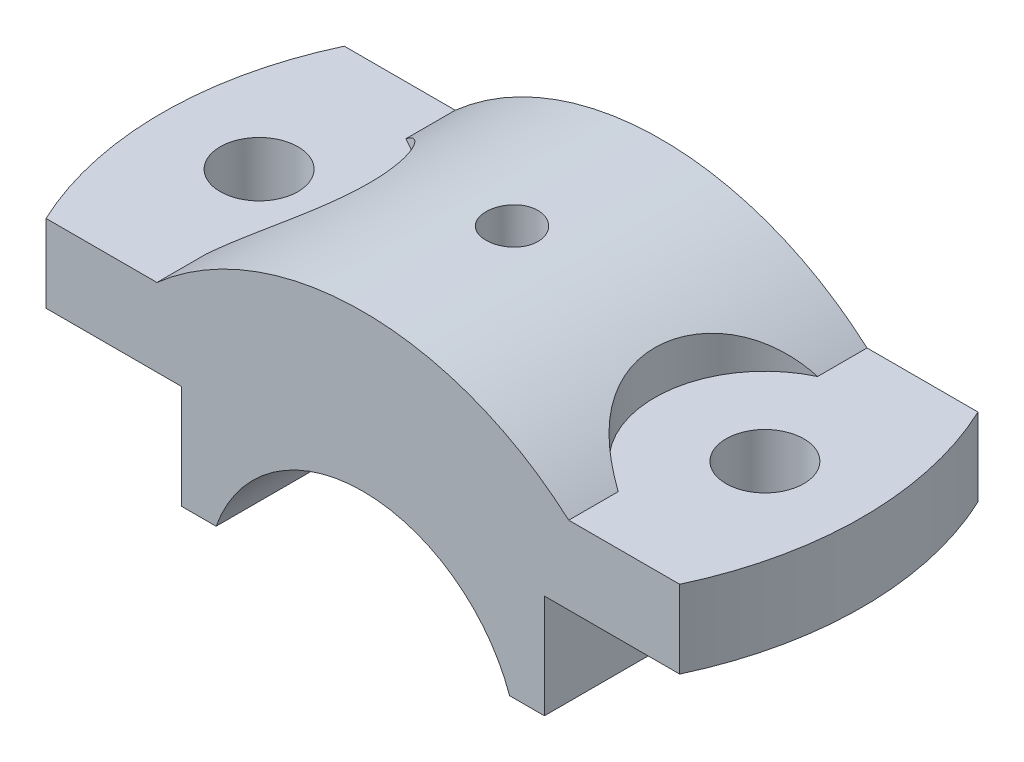
SolidWorks part; units mm, degrees
material "Gray Cast Iron"
ref_plane "Front Plane" through (0, 0, 0) normal (0, 0, 1) x (1, 0, 0)
ref_plane "Top Plane" through (0, 0, 0) normal (0, 1, 0) x (1, 0, 0)
ref_plane "Right Plane" through (0, 0, 0) normal (1, 0, 0) x (0, 0, -1)
sketch "Sketch1" plane through (0, 0, 0) normal (0, 1, 0) x (1, 0, 0)
  line L1 (-48.8569, 23) -> (48.8569, 23)
  line L3 (-48.8569, -23) -> (48.8569, -23)
  line L5 (0, -23) -> (0, 23) construction
  line L6 (-54, 0) -> (54, 0) construction
  arc A0 (-48.8569, 23) -> (-48.8569, -23) centre (0, 0) ccw
  arc A1 (48.8569, -23) -> (48.8569, 23) centre (0, 0) ccw
  point P0 (0, 0)
  dimension "D3" = 108
  dimension "D1" = 48.8569
extrude "Boss-Extrude1" add sketch "Sketch1" along normal blind 12
sketch "Sketch2" plane through (0, 0, 23) normal (0, 0, 1) x (1, 0, 0)
  line L0 (0, 29.7823) -> (0, -29.7823) construction
  line L2 (-28, 0.5) -> (28, 0.5)
  line L3 (-28, 0.5) -> (-28, -16)
  line L4 (-28, -16) -> (-22.6274, -16)
  line L5 (28, 0.5) -> (28, -16)
  line L6 (0, -16) -> (0, 0.5) construction
  line L7 (-28, -7.75) -> (28, -7.75) construction
  line L8 (-48.8569, 12) -> (48.8569, 12) construction
  line L9 (22.6274, -16) -> (28, -16)
  arc A0 (22.6274, -16) -> (-22.6274, -16) centre (0, -24) ccw
  point P0 (0, -7.75)
  point P4 (0, 0)
  dimension "D4" = 24
  dimension "D1" = 11.5
  dimension "D2" = 16.5
  dimension "D3" = 56
  dimension "D5" = 8
extrude "Boss-Extrude2" add sketch "Sketch2" against normal up to surface (46 mm away) up to face at (0, 6, -23)
sketch "Sketch3" plane through (0, 0, 23) normal (0, 0, 1) x (1, 0, 0)
  line L0 (0, 40.5216) -> (0, -40.5216) construction
  line L2 (-28, -16) -> (-22.6274, -16) construction
  line L3 (-31.749, 12) -> (31.749, 12)
  line L4 (-48.8569, 12) -> (48.8569, 12) construction
  arc A0 (31.749, 12) -> (-31.749, 12) centre (0, -24) ccw
  point P6 (0, 0)
  dimension "D1" = 48
  dimension "D2" = 0
  dimension "D3" = 8
extrude "Boss-Extrude4" add sketch "Sketch3" against normal up to surface (46 mm away) contours A0 L3 up to face at (0, -2.4, -23)
sketch "Sketch4" plane through (0, 12, 0) normal (0, 1, 0) x (1, 0, 0)
  line L0 (0, 32.3581) -> (0, -32.3581) construction
  line L1 (-61.0068, 0) -> (61.0068, 0) construction
  circle A0 centre (39, 0) radius 6
  circle A1 centre (-39, 0) radius 6
  point P5 (0, 0)
  point P9 (0, 0)
  dimension "D1" = 12
  dimension "D2" = 39
extrude "Cut-Extrude1" cut sketch "Sketch4" against normal through all
sketch "Sketch5" plane through (0, 12, 0) normal (0, 1, 0) x (1, 0, 0)
  line L0 (-31.749, 15.3761) -> (-31.749, -15.3761)
  line L1 (31.749, 23) -> (31.749, -23) construction
  line L2 (31.749, 15.3761) -> (31.749, -15.3761)
  line L3 (0, 28.2492) -> (0, -28.2492) construction
  arc A0 (31.749, 15.3761) -> (31.749, -15.3761) centre (39, 0) ccw
  arc A1 (-31.749, 15.3761) -> (-31.749, -15.3761) centre (-39, 0) cw
  point P14 (0, 0)
  dimension "D1" = 17
extrude "Cut-Extrude4" cut sketch "Sketch5" along normal through all
sketch "Sketch6" plane through (0, 12, 0) normal (0, 1, 0) x (1, 0, 0)
  circle A0 centre (0, 0) radius 3
  dimension "D1" = 6
extrude "Cut-Extrude5" cut sketch "Sketch6" against normal through all both and the other way through all
ref_plane "Plane4" through (0, 24, 0) normal (0, 1, 0) x (1, 0, 0)
sketch "Sketch10" plane through (0, 24, 0) normal (0, 1, 0) x (1, 0, 0)
  circle A0 centre (0, 0) radius 4
  dimension "D1" = 8
extrude "Cut-Extrude6" cut sketch "Sketch10" against normal blind 16
